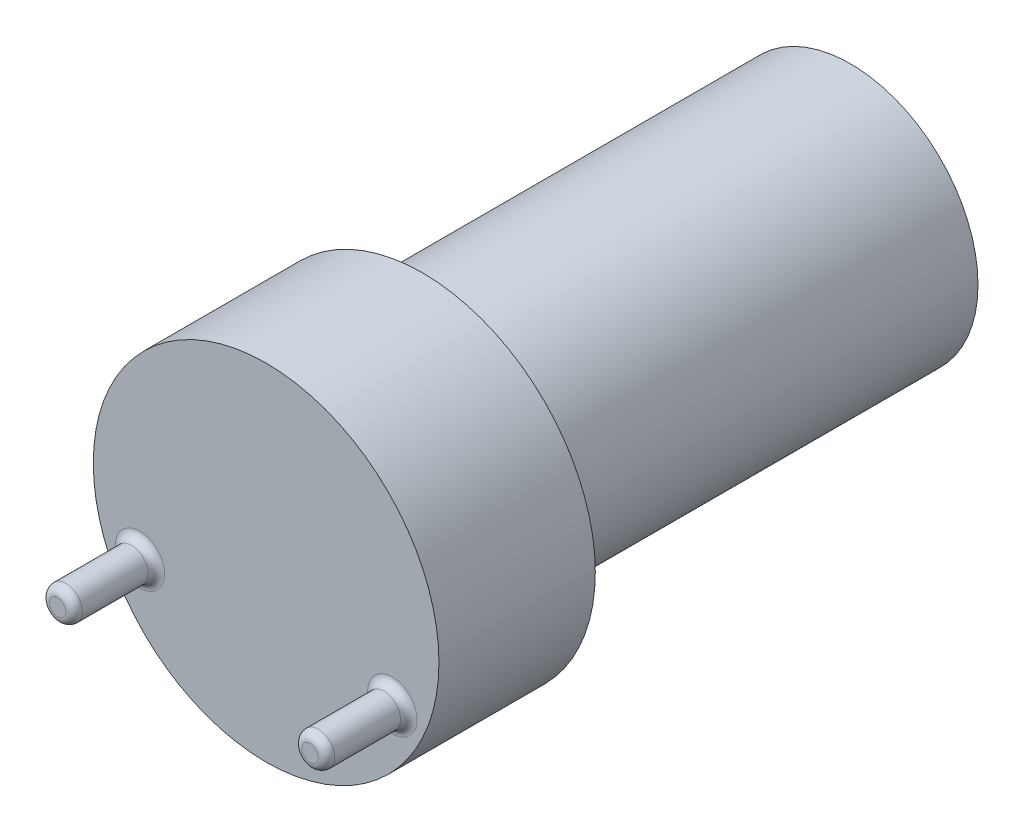
SolidWorks part; units mm, degrees
ref_plane "Front Plane" through (0, 0, 0) normal (0, 0, 1) x (1, 0, 0)
ref_plane "Top Plane" through (0, 0, 0) normal (0, 1, 0) x (1, 0, 0)
ref_plane "Right Plane" through (0, 0, 0) normal (1, 0, 0) x (0, 0, -1)
sketch "Sketch1" plane through (0, 0, 0) normal (0, 0, 1) x (1, 0, 0)
  circle A0 centre (0, 0) radius 15.5
  dimension "D1" = 31
extrude "Boss-Extrude1" add sketch "Sketch1" along normal blind 52
sketch "Sketch2" plane through (0, 0, 52) normal (0, 0, 1) x (1, 0, 0)
  line L0 (0, 15.5) -> (0, -15.5) construction
  circle A0 centre (0, 0) radius 15.5 construction
  circle A1 centre (0, -1.5) radius 21
  point P7 (0, 0)
  dimension "D1" = 42
  dimension "D2" = 1.5
extrude "Boss-Extrude2" add sketch "Sketch2" along normal blind 19
sketch "Sketch3" plane through (0, 0, 71) normal (0, 0, 1) x (1, 0, 0)
  line L0 (0, 19.5) -> (0, 0) construction
  line L1 (0, 0) -> (18.8012, -10.8549) construction
  line L2 (0, 0) -> (-18.8012, -10.8549) construction
  circle A0 centre (0, -1.5) radius 21 construction
  circle A1 centre (-15.3371, -8.8549) radius 2
  circle A2 centre (15.3371, -8.8549) radius 2
  dimension "D2" = 4
  dimension "D1" = 120
  dimension "D3" = 4
extrude "Boss-Extrude3" add sketch "Sketch3" along normal blind 10
fillet "Fillet1" radius 1 4 edges at (13.3371, -8.8549, 81) (-13.3371, -8.8549, 81) (-13.3371, -8.8549, 71) (13.3371, -8.8549, 71)
